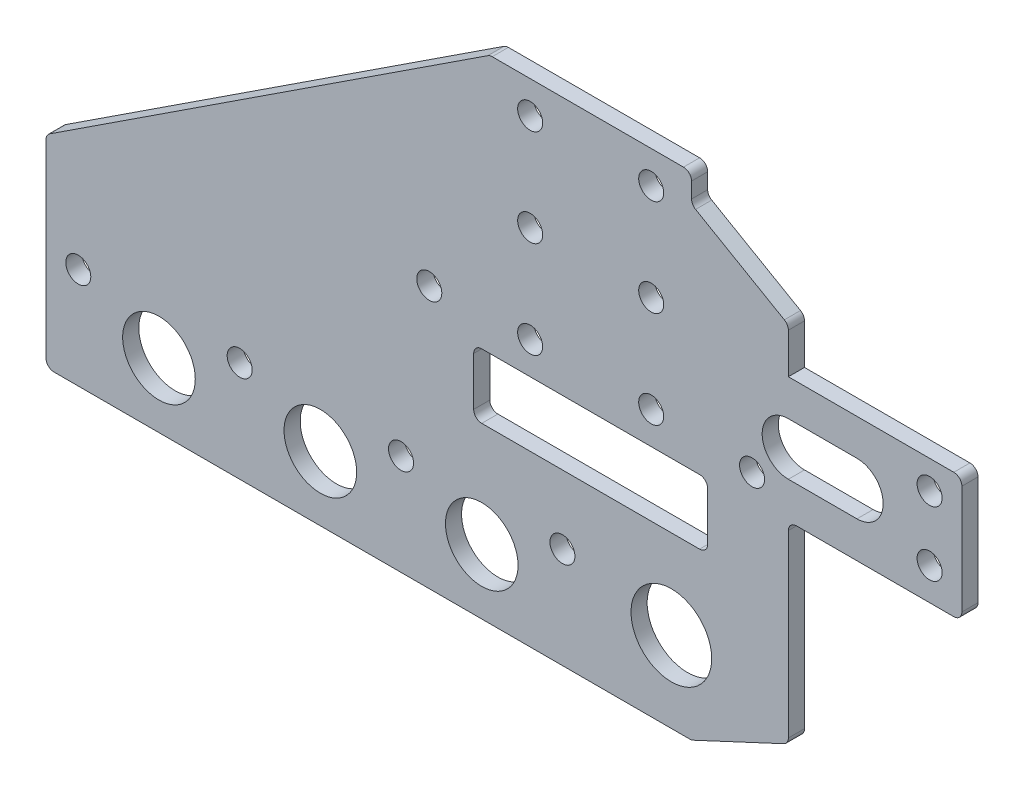
SolidWorks part; units mm, degrees
material "Thornel Mat VMA"
ref_plane "前视基准面" through (0, 0, 0) normal (0, 0, 1) x (1, 0, 0)
ref_plane "上视基准面" through (0, 0, 0) normal (0, 1, 0) x (1, 0, 0)
ref_plane "右视基准面" through (0, 0, 0) normal (1, 0, 0) x (0, 0, -1)
sketch "草图1" plane through (0, 0, 0) normal (0, 0, 1) x (1, 0, 0)
  line L0 (0, 0) -> (-80, 0)
  line L2 (0, 61) -> (0, 57.5)
  line L3 (0, 61) -> (-25, 61)
  line L4 (-25, 61) -> (-80, 25)
  line L5 (-80, 25) -> (-80, 0)
  line L6 (-80, 12.5) -> (0, 12.5) construction
  line L7 (-12.5, 0) -> (-12.5, 99.2299) construction
  line L68 (33.5, 45) -> (33.5, 29.5)
  line L71 (0, 0) -> (-25, 25) construction
  line L80 (-25, 61) -> (-25, 25) construction
  line L82 (-25, 25) -> (-80, 25) construction
  line L83 (-25, 25) -> (0, 25) construction
  line L84 (0, 57.5) -> (12, 50.5718)
  line L85 (2, 21) -> (-27, 21)
  line L86 (2, 21) -> (2, 29)
  line L87 (2, 29) -> (-27, 29)
  line L88 (-27, 21) -> (-27, 29)
  line L89 (2, 21) -> (-27, 29) construction
  line L90 (2, 29) -> (-27, 21) construction
  line L91 (12, 50.5718) -> (12, 45)
  line L92 (12, 5.5957) -> (0, 0)
  line L93 (2, 25) -> (12, 25) construction
  line L94 (0, 12.5) -> (0, 0) construction
  line L95 (33.5, 29.5) -> (12, 29.5)
  line L101 (20.5, 37.25) -> (12, 37.25) construction
  line L104 (20.5, 34) -> (12, 34)
  line L109 (-35, 42.5029) -> (-43.4071, 37) construction
  line L110 (-43.4071, 37) -> (-35, 37) construction
  line L112 (-35, 42.5029) -> (-35, 37) construction
  line L113 (20.5, 40.5) -> (12, 40.5)
  line L134 (12, 45) -> (33.5, 45)
  line L136 (12, 5.5957) -> (12, 29.5)
  circle A1 centre (-36, 12.5) radius 1.55
  circle A2 centre (-96, 12.5) radius 1.55 construction
  circle A3 centre (-56, 12.5) radius 1.55
  circle A4 centre (-76, 12.5) radius 1.55
  circle A28 centre (-16, 12.5) radius 1.55
  circle A31 centre (29.5, 41.5) radius 1.55
  circle A32 centre (29.5, 33.5) radius 1.55
  circle A33 centre (-5, 33) radius 1.55
  circle A34 centre (-20, 33) radius 1.55
  circle A35 centre (-5, 45) radius 1.55
  circle A36 centre (-20, 45) radius 1.55
  circle A37 centre (-5, 57) radius 1.55
  circle A38 centre (-20, 57) radius 1.55
  circle A42 centre (-26, 8) radius 4.5
  circle A43 centre (-46, 8) radius 4.5
  circle A44 centre (-66, 8) radius 4.5
  circle A45 centre (-86, 8) radius 4.5 construction
  circle A46 centre (-2.5, 10) radius 5
  circle A47 centre (-32.5, 32.5) radius 1.55
  circle A48 centre (7.5, 32.5) radius 1.55
  arc A49 (20.5, 34) -> (20.5, 40.5) centre (20.5, 37.25) ccw
  arc A50 (12, 40.5) -> (12, 34) centre (12, 37.25) ccw
  point P22 (-12.5, 12.5)
  point P31 (-12.5, 25)
  point P63 (16.25, 37.25)
  dimension "D6" = 3.1
  dimension "D14" = 3.1
  dimension "D8" = 20
  dimension "D13" = 8
  dimension "D23" = 7.5
  dimension "D33" = 3.1
  dimension "D34" = 8
  dimension "D26" = 4
  dimension "D28" = 9
  dimension "D39" = 10
  dimension "D19" = 3.1
  dimension "D25" = 42
  dimension "D1" = 61
  dimension "D2" = 25
  dimension "D3" = 80
  dimension "D4" = 25
  dimension "D5" = 25
  dimension "D7" = 3.5
  dimension "D9" = 20
  dimension "D10" = 20
  dimension "D11" = 2
  dimension "D12" = 8
  dimension "D15" = 15
  dimension "D16" = 12
  dimension "D17" = 12
  dimension "D18" = 33.5
  dimension "D20" = 10
  dimension "D21" = 65
  dimension "D22" = 60
  dimension "D24" = 7.5
  dimension "D27" = 8
  dimension "D29" = 10
  dimension "D30" = 12
  dimension "D31" = 10
  dimension "D32" = 20
  dimension "D35" = 10
  dimension "D36" = 4
  dimension "D37" = 20
  dimension "D38" = 10
  dimension "D40" = 10
  dimension "D41" = 4
  dimension "D42" = 3.5
  dimension "D43" = 3.5
  dimension "D44" = 4.5
  dimension "D45" = 4.5
  dimension "D46" = 9
  dimension "D47" = 12
extrude "凸台-拉伸1" add sketch "草图1" along normal blind 2
fillet "圆角1" radius 1 15 edges at (0, 0, 1) (-80, 0, 1) (-80, 25, 1) (-25, 61, 1) (0, 61, 1) (12, 50.5718, 1) (-27, 29, 1) (2, 29, 1) (2, 21, 1) (-27, 21, 1) (0, 57.5, 1) (33.5, 29.5, 1) (33.5, 45, 1) (12, 29.5, 1) (12, 5.5957, 1)
